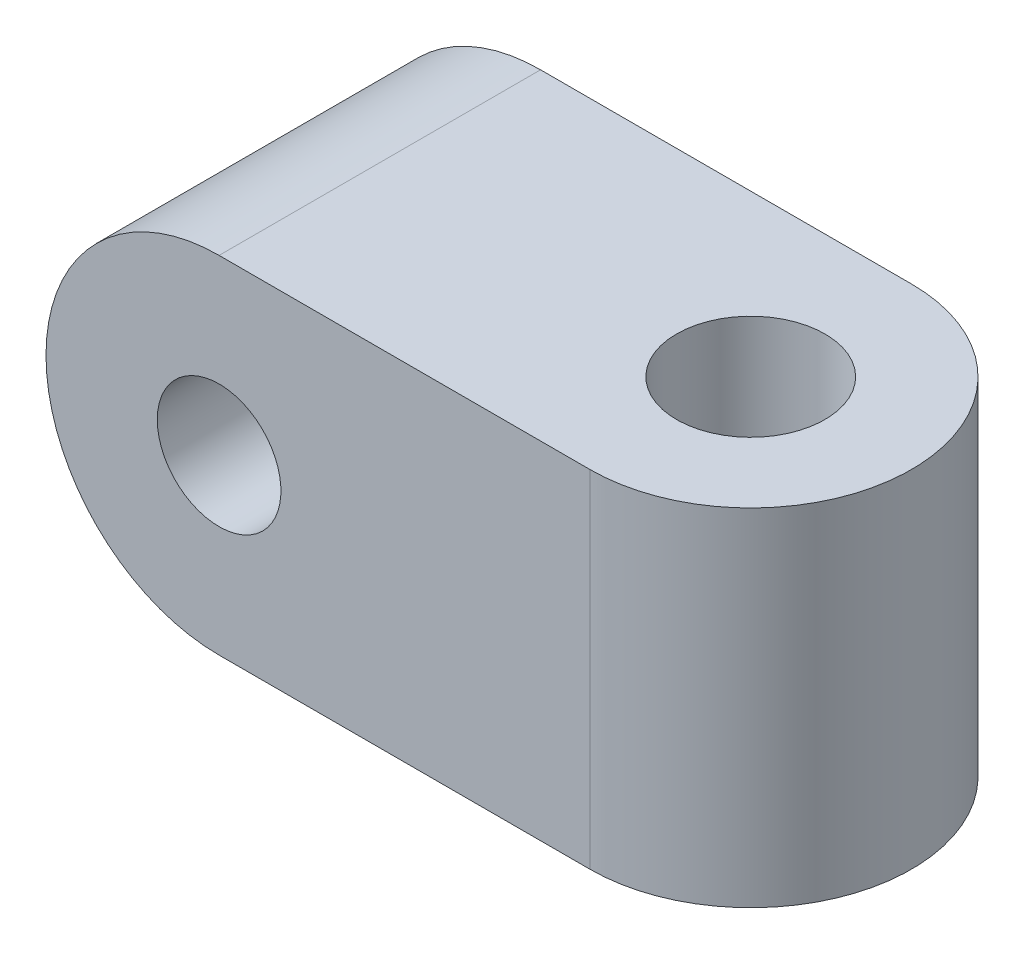
SolidWorks part; units mm, degrees
ref_plane "Front" through (0, 0, 0) normal (0, 0, 1) x (1, 0, 0)
ref_plane "Top" through (0, 0, 0) normal (0, 1, 0) x (1, 0, 0)
ref_plane "Right" through (0, 0, 0) normal (1, 0, 0) x (0, 0, -1)
sketch "Эскиз1" plane through (0, 0, 0) normal (0, 0, 1) x (1, 0, 0)
  line L0 (0, 3.5) -> (3.5, 3.5)
  line L1 (3.5, 3.5) -> (3.5, -3.5)
  line L2 (3.5, -3.5) -> (0, -3.5)
  circle A0 centre (0, 0) radius 1.25
  circle A1 centre (0, 0) radius 3.5
  dimension "D1" = 2.5
  dimension "D2" = 7
extrude "Бобышка-Вытянуть1" add sketch "Эскиз1" along normal blind 6.5 contours A1 A0 | A1 L1 L0 | A1 L2 L1
sketch "Эскиз2" plane through (0, 3.5, 0) normal (0, 1, 0) x (1, 0, 0)
  line L0 (3.5, -6.5) -> (3.5, 0) construction
  line L1 (7.5, 0) -> (3.5, 0)
  line L2 (3.5, 0) -> (3.5, -6.5)
  line L3 (3.5, -6.5) -> (7.5, -6.5)
  circle A0 centre (7.5, -3.25) radius 1.5
  circle A1 centre (7.5, -3.25) radius 3.25
  point P2 (3.5, -3.25)
  line M7 (3.5, -6.5) -> (3.5, 0)
  dimension "D1" = 3
  dimension "D3" = 4
  dimension "D2" = 6.5
extrude "Бобышка-Вытянуть2" add sketch "Эскиз2" against normal blind 7 contours A1 L1 L3 M7 | A1 A0
